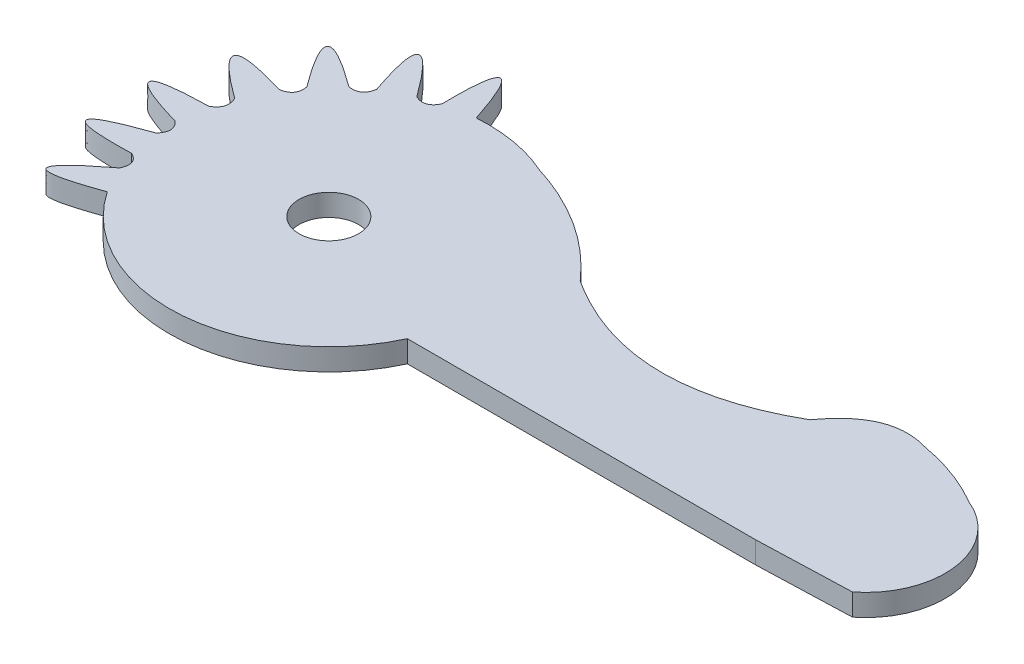
SolidWorks part; units mm, degrees
ref_plane "前视基准面" through (0, 0, 0) normal (0, 0, 1) x (1, 0, 0)
ref_plane "上视基准面" through (0, 0, 0) normal (0, 1, 0) x (1, 0, 0)
ref_plane "右视基准面" through (0, 0, 0) normal (1, 0, 0) x (0, 0, -1)
sketch "草图1" plane through (0, 0, 0) normal (0, 1, 0) x (1, 0, 0)
  line L0 (14.611, -6.7) -> (49.6904, -6.7)
  line L2 (49.6904, -6.7) -> (59.1421, -6.3765)
  arc A0 (6.5551, 14.6766) -> (-1.174, 16.031) centre (0, 0) ccw
  arc A1 (59.1421, -6.3765) -> (57.1955, 7.3271) centre (54.1955, -0.0891) ccw
  arc A4 (-13.3181, -9) -> (14.611, -6.7) centre (0, 0) ccw
  circle A15 centre (0, 0) radius 3
  spline S0 degree 3 poles (50.3471, 9.8802) (52.7614, 9.4439) (55.0442, 8.5928) (57.1955, 7.3271) knots 0.288437 0.288437 0.288437 0.288437 1 1 1 1
  spline S1 degree 2 poles (-14.7879, -6.3) (-14.1793, -5.0235) (-15.4558, -4.4148) knots 0 0 0 1 1 1
  spline S2 degree 2 poles (-13.3181, -9) (-22.836, -12.4311) (-14.7879, -6.3) knots 0 0 0 1 1 1
  spline S3 degree 2 poles (6.5551, 14.6766) (13.509, 12.4928) (18.294, 7.0371) knots 0 0 0 1 1 1
  spline S4 degree 2 poles (-15.4558, -4.4148) (-25.5664, -4.7364) (-16.0116, -1.4148) knots 0 0 0 1 1 1
  spline S5 degree 2 poles (-16.0116, -1.4148) (-15.0379, -0.3941) (-16.0633, 0.5852) knots 0 0 0 1 1 1
  spline S6 degree 2 poles (-16.0633, 0.5852) (-25.7809, 3.3882) (-15.669, 3.5852) knots 0 0 0 1 1 1
  spline S7 degree 2 poles (-15.669, 3.5852) (-14.4125, 4.2993) (-15.0724, 5.5852) knots 0 0 0 1 1 1
  spline S8 degree 2 poles (-15.0724, 5.5852) (-23.2951, 11.5171) (-13.5892, 8.5852) knots 0 0 0 1 1 1
  spline S9 degree 2 poles (-13.5892, 8.5852) (-12.193, 8.8101) (-12.4179, 10.2063) knots 0 0 0 1 1 1
  spline S10 degree 2 poles (-12.4179, 10.2063) (-18.4607, 18.314) (-10.305, 12.3361) knots 0 0 0 1 1 1
  spline S11 degree 2 poles (-10.305, 12.3361) (-8.9071, 12.1223) (-8.6933, 13.5203) knots 0 0 0 1 1 1
  spline S12 degree 2 poles (-8.6933, 13.5203) (-11.9612, 23.0896) (-6.0295, 14.9002) knots 0 0 0 1 1 1
  spline S13 degree 2 poles (-6.0295, 14.9002) (-4.7643, 14.2684) (-4.1325, 15.5337) knots 0 0 0 1 1 1
  spline S14 degree 2 poles (-4.1325, 15.5337) (-4.3112, 25.644) (-1.174, 16.031) knots 0 0 0 1 1 1
  spline S15 degree 3 poles (41.9844, 6.5142) (43.667, 8.849) (46.3171, 10.5568) (49.3037, 10.1961) (50.3471, 9.8802) knots 0.090085 0.090085 0.090085 0.090085 0.520369 0.736119 0.736119 0.736119 0.736119
  spline S16 degree 2 poles (18.294, 7.0371) (29.824, -0.4499) (41.9844, 6.5142) knots 0 0 0 1 1 1
  point P1 (-13.3181, -9)
  point P3 (0, -6.7)
  point P6 (54.1955, -0.0891)
  point P7 (49.6904, -6.7)
  point P8 (51.3181, 4)
  point P9 (57.1955, -0.0891)
  point P12 (54.0636, 4)
  point P13 (-14.7879, -6.3)
  point P15 (32.3181, 6.3)
  point P17 (-18.4445, -10.0406)
  point P24 (-15.4558, -4.4148)
  point P25 (-16.0633, 0.5852)
  point P26 (-16.0116, -1.4148)
  point P27 (-15.669, 3.5852)
  point P28 (-15.0724, 5.5852)
  point P29 (-13.5892, 8.5852)
  point P30 (-12.4179, 10.2063)
  point P31 (-10.305, 12.3361)
  point P32 (-8.6933, 13.5203)
  point P33 (-6.0295, 14.9002)
  point P34 (-4.1325, 15.5337)
  point P35 (-1.174, 16.031)
  point P41 (0, 8.4)
  point P49 (8.4, 0)
  point P51 (-8.4, 0)
  point P52 (0, -8.4)
  point P53 (0, 5)
  point P56 (-5, 0)
  point P58 (0, -5)
  point P60 (5, 0)
  point P61 (0, 6.7)
  point P62 (6.7, 0)
  point P64 (-6.7, 0)
  dimension "D1" = 6.7
  dimension "D6" = 5
  dimension "D2" = 8
  dimension "D3" = 5
  dimension "D4" = 3
  dimension "D5" = 13
  dimension "D7" = 5
  dimension "D8" = 5
  dimension "D9" = 5
  dimension "D10" = 1.7
  dimension "D11" = 1.7
  dimension "D12" = 1.7
  dimension "D13" = 1.7
  dimension "D14" = 1.7
  dimension "D15" = 1.7
  dimension "D16" = 1.7
extrude "凸台-拉伸1" add sketch "草图1" along normal blind 2.2
